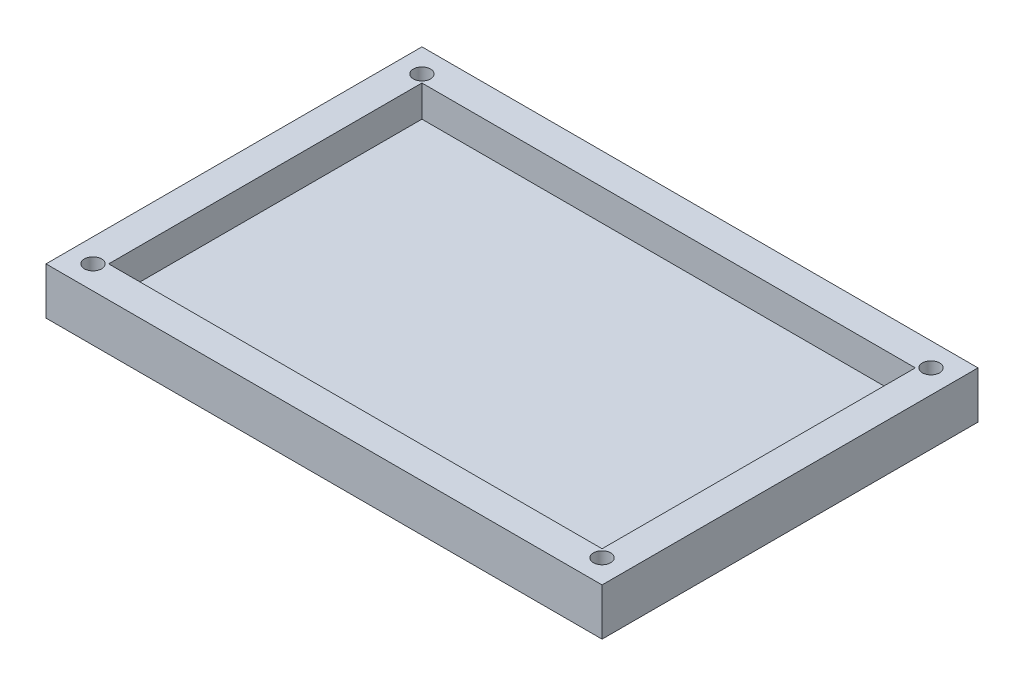
SolidWorks part; units mm, degrees
ref_plane "前视基准面" through (0, 0, 0) normal (0, 0, 1) x (1, 0, 0)
ref_plane "上视基准面" through (0, 0, 0) normal (0, 1, 0) x (1, 0, 0)
ref_plane "右视基准面" through (0, 0, 0) normal (1, 0, 0) x (0, 0, -1)
sketch "草图1" plane through (0, 0, 0) normal (0, 1, 0) x (1, 0, 0)
  line L1 (-17.75, 12) -> (17.75, 12)
  line L2 (-17.75, 12) -> (-17.75, -12)
  line L3 (-17.75, -12) -> (17.75, -12)
  line L4 (17.75, 12) -> (17.75, -12)
  line L5 (-17.75, 12) -> (17.75, -12) construction
  line L6 (-17.75, -12) -> (17.75, 12) construction
  point P0 (0, 0)
  dimension "D1" = 24
  dimension "D2" = 35.5
extrude "凸台-拉伸1" add sketch "草图1" along normal blind 3
sketch "草图2" plane through (0, 3, 0) normal (0, 1, 0) x (1, 0, 0)
  line L0 (17.75, 12) -> (-17.75, 12) construction
  line L1 (-15.75, 10) -> (15.75, 10)
  line L2 (-15.75, 10) -> (-15.75, -10)
  line L3 (-15.75, -10) -> (15.75, -10)
  line L4 (15.75, 10) -> (15.75, -10)
  line L5 (-15.75, 10) -> (15.75, -10) construction
  line L6 (-15.75, -10) -> (15.75, 10) construction
  line L7 (-17.75, 12) -> (-17.75, -12) construction
  point P0 (0, 0)
  dimension "D1" = 2
  dimension "D2" = 2
extrude "切除-拉伸1" cut sketch "草图2" against normal blind 2
sketch "草图3" plane through (0, 3, 0) normal (0, 1, 0) x (1, 0, 0)
  line L0 (17.75, 12) -> (-17.75, 12) construction
  line L1 (-17.75, 12) -> (-17.75, -12) construction
  line L2 (-17.75, -12) -> (17.75, -12) construction
  line L3 (17.75, -12) -> (17.75, 12) construction
  circle A0 centre (-16.25, 10.5) radius 0.55
  circle A1 centre (-16.25, -10.5) radius 0.55
  circle A2 centre (16.25, -10.5) radius 0.55
  circle A3 centre (16.25, 10.5) radius 0.55
  point P12 (0, 0)
  point P14 (-16.1327, -11.5347)
  dimension "D3" = 1.1
  dimension "D10" = 1.1
  dimension "D11" = 1.1
  dimension "D12" = 1.1
  dimension "D1" = 1.5
  dimension "D2" = 1.5
  dimension "D4" = 1.5
  dimension "D5" = 1.5
  dimension "D6" = 1.5
  dimension "D7" = 1.5
  dimension "D8" = 1.5
  dimension "D9" = 1.5
extrude "切除-拉伸2" cut sketch "草图3" against normal blind 2
